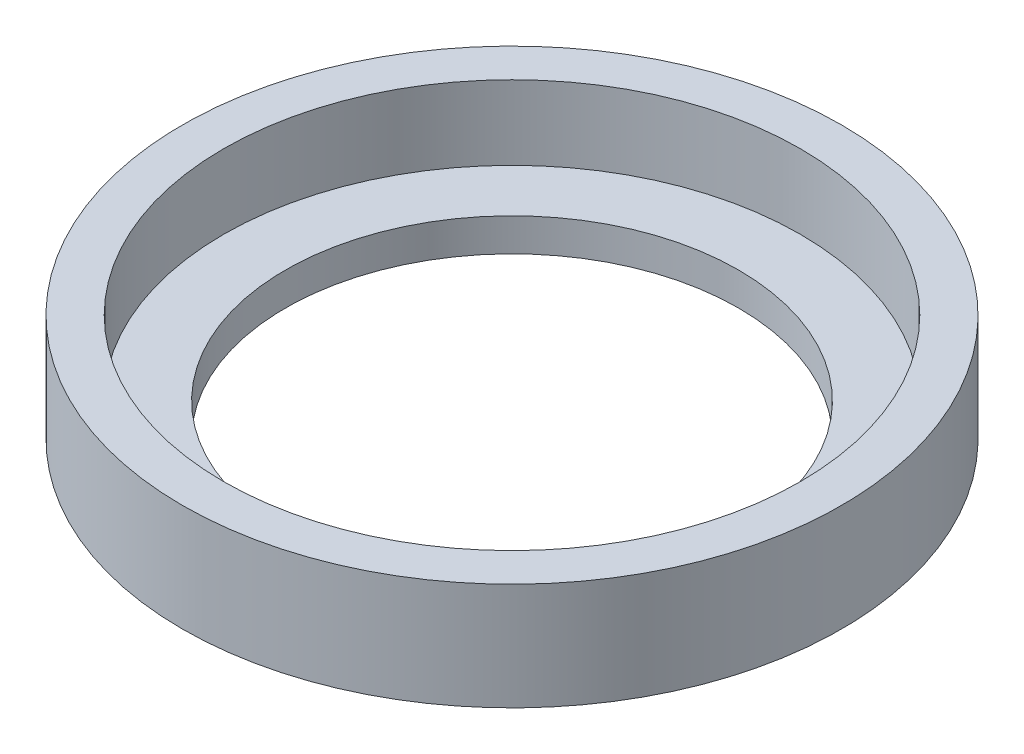
SolidWorks part; units mm, degrees
ref_plane "前视" through (0, 0, 0) normal (0, 0, 1) x (1, 0, 0)
ref_plane "上视" through (0, 0, 0) normal (0, 1, 0) x (1, 0, 0)
ref_plane "右视" through (0, 0, 0) normal (1, 0, 0) x (0, 0, -1)
sketch "草图1" plane through (0, 0, 0) normal (0, 1, 0) x (1, 0, 0)
  circle A0 centre (0, 0) radius 35
  circle A1 centre (0, 0) radius 40
  dimension "D1" = 70
  dimension "D2" = 80
extrude "凸台-拉伸1" add sketch "草图1" along normal blind 9
sketch "草图2" plane through (0, 0, 0) normal (0, -1, 0) x (1, 0, 0)
  circle A0 centre (0, 0) radius 27.5
  circle A1 centre (0, 0) radius 40
  dimension "D1" = 55
extrude "凸台-拉伸2" add sketch "草图2" along normal blind 4
